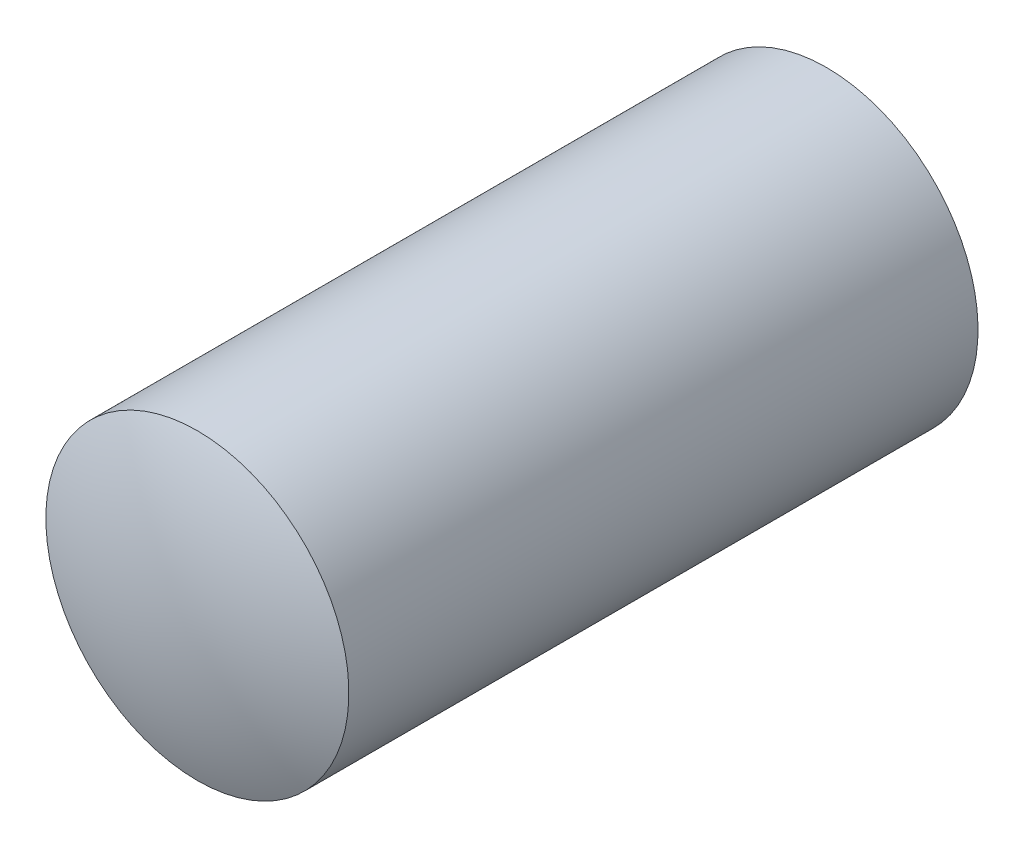
SolidWorks part; units mm, degrees
ref_plane "Front Plane" through (0, 0, 0) normal (0, 0, 1) x (1, 0, 0)
ref_plane "Top Plane" through (0, 0, 0) normal (0, 1, 0) x (1, 0, 0)
ref_plane "Right Plane" through (0, 0, 0) normal (1, 0, 0) x (0, 0, -1)
sketch "Sketch3" plane through (0, 0, 0) normal (1, 0, 0) x (0, 0, -1)
  line L3 (0, 0) -> (-11.8729, 0)
  line L4 (0, 0) -> (5, 0)
  line L5 (0, 0) -> (-1.8729, 0)
  line L6 (5, 0) -> (5, 3.875)
  line L7 (5, 3.875) -> (-13.431, 3.875)
  arc A2 (0, 0) -> (0.3907, 1.9375) centre (5, 0) cw
  arc A3 (-11.8729, 0) -> (-11.0915, 3.875) centre (-1.8729, 0) cw
  dimension "D7" = 10
  dimension "D5" = 5
  dimension "D1" = 5
  dimension "D3" = 1.8729
  dimension "D6" = 3.875
revolve "Revolve1" add sketch "Sketch3" angle 360 about L3
equation "\"T_c\"= ( 1 + 1 / \"n\" ) * \"R_2\" - \"R_1\""
equation "\"R_1\"= \"gloabl_scale\" * 5mm"
equation "\"h\"= \"gloabl_scale\" * 7.75 / 2mm"
equation "\"gloabl_scale\"= 1"
equation "\"R_2\"= \"gloabl_scale\" * 10mm"
equation "\"x_origin_1\"= \"R_1\""
equation "\"x_origin_2\"= \"R_2\" - \"T_c\""
equation "\"T_edge\"= \"T_c\" - \"R_2\" * ( 1 - sqr ( 1 - \"h\" ^ 2 / \"R_2\" ^ 2 ) ) + 2mm"
equation "\"D1@Sketch3\"=\"R_1\""
equation "\"D3@Sketch3\"=\"R_2\"-\"T_c\""
equation "\"D7@Sketch3\"=\"R_2\""
equation "\"D5@Sketch3\"=\"R_1\""
equation "\"D6@Sketch3\"=\"h\""
equation "\"n\"= 1.455"
